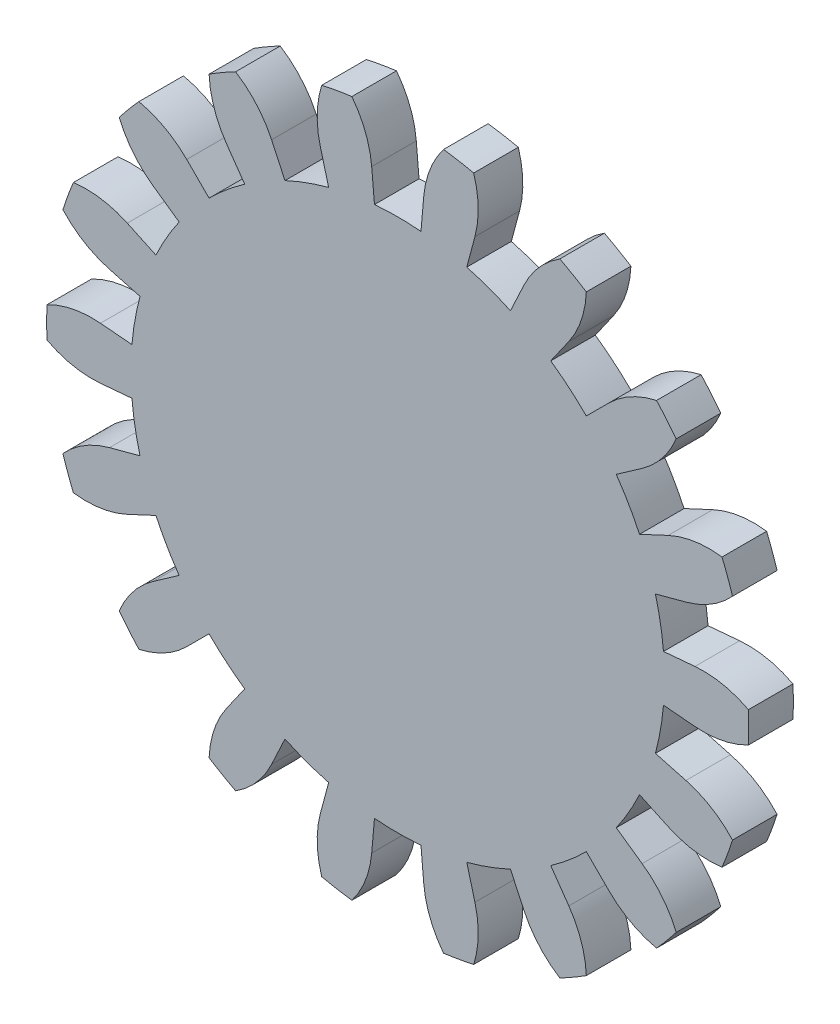
SolidWorks part; units mm, degrees
ref_plane "Front Plane" through (0, 0, 0) normal (0, 0, 1) x (1, 0, 0)
ref_plane "Top Plane" through (0, 0, 0) normal (0, 1, 0) x (1, 0, 0)
ref_plane "Right Plane" through (0, 0, 0) normal (1, 0, 0) x (0, 0, -1)
sketch "Sketch4" plane through (0, 0, 0) normal (0, 0, 1) x (1, 0, 0)
  line L0 (0, 0) -> (70.055, 0) construction
  line L1 (0, 0) -> (57.3139, 2.5024) construction
  line L2 (0, 0) -> (61.7902, 5.4059) construction
  line L3 (0, 0) -> (70.6997, 12.4663) construction
  line L4 (42.3383, 3.7041) -> (37.8554, 3.3119)
  line L5 (0, 0) -> (37.4227, 6.5986)
  line L6 (42.3383, -3.7041) -> (37.8554, -3.3119)
  line L7 (0, 0) -> (37.4227, -6.5986)
  arc A0 (49.9524, -2.181) -> (49.9524, 2.181) centre (0, 0) ccw
  circle A1 centre (0, 0) radius 42.5 construction
  arc A3 (42.3383, 3.7041) -> (49.9524, 2.181) centre (43.543, -10.0663) cw
  arc A5 (37.8554, 3.3119) -> (37.4227, 6.5986) centre (0, 0) ccw construction
  arc A6 (37.8554, 3.3119) -> (37.4227, 6.5986) centre (0, 0) ccw
  arc A7 (42.3383, -3.7041) -> (49.9524, -2.181) centre (43.543, 10.0663) ccw
  arc A8 (37.8554, -3.3119) -> (37.4227, -6.5986) centre (0, 0) cw
  dimension "D1" = 38
  dimension "D2" = 85
  dimension "D3" = 100
  dimension "D4" = 2.5
  dimension "D5" = 5
  dimension "D6" = 10
extrude "Boss-Extrude2" add sketch "Sketch4" along normal blind 6.35
pattern_circular "CirPattern1" count 18 over 360 about axis through (0, 0, 0) along (0, 0, 1) of "Boss-Extrude2"
